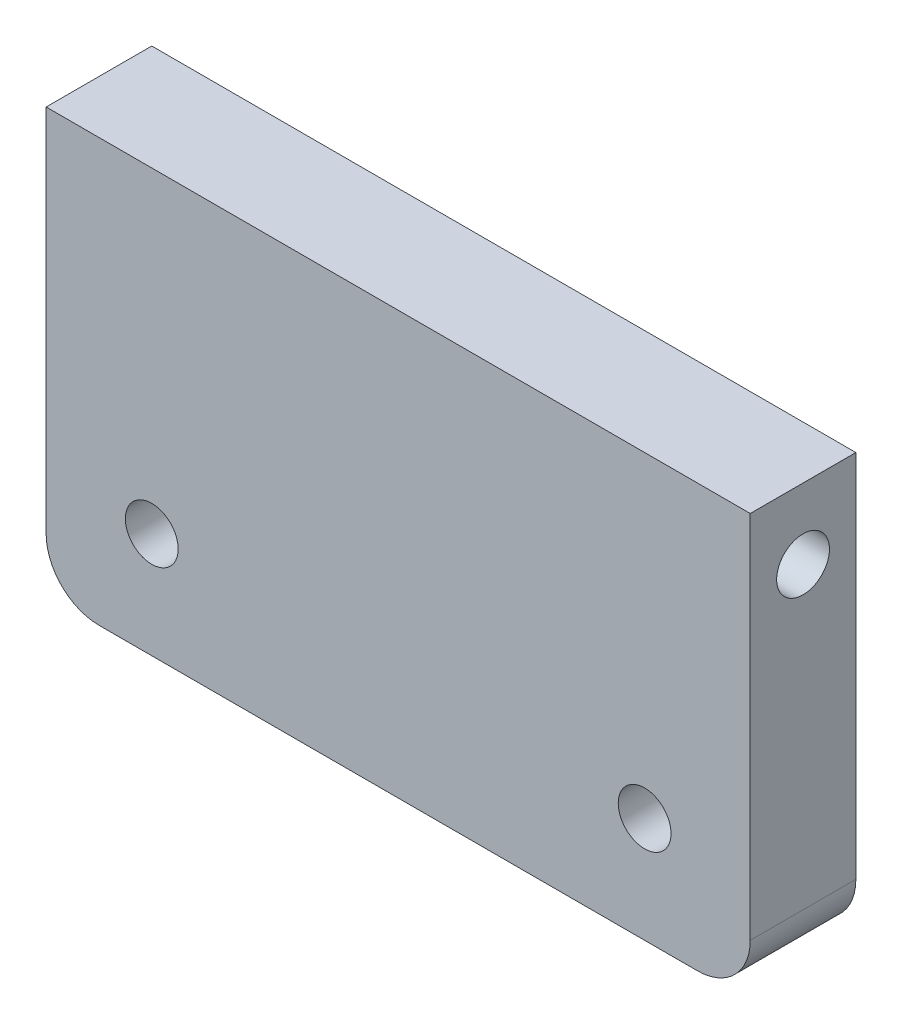
SolidWorks part; units mm, degrees
ref_plane "Front Plane" through (0, 0, 0) normal (0, 0, 1) x (1, 0, 0)
ref_plane "Top Plane" through (0, 0, 0) normal (0, 1, 0) x (1, 0, 0)
ref_plane "Right Plane" through (0, 0, 0) normal (1, 0, 0) x (0, 0, -1)
sketch "Sketch2" plane through (0, 0, 0) normal (0, 0, 1) x (1, 0, 0)
  line L0 (0, 38.1) -> (0, -38.1) construction
  line L1 (-63.5, 38.1) -> (63.5, 38.1)
  line L2 (-63.5, 38.1) -> (-63.5, -28.575)
  line L3 (-53.975, -38.1) -> (53.975, -38.1)
  line L4 (63.5, 38.1) -> (63.5, -28.575)
  line L5 (-63.5, 38.1) -> (63.5, -38.1) construction
  line L6 (-63.5, -38.1) -> (63.5, 38.1) construction
  circle A0 centre (-44.45, -19.05) radius 4.7625
  circle A1 centre (44.45, -19.05) radius 4.7625
  arc A2 (63.5, -28.575) -> (53.975, -38.1) centre (53.975, -28.575) cw
  arc A3 (-63.5, -28.575) -> (-53.975, -38.1) centre (-53.975, -28.575) ccw
  point P0 (0, 0)
  point P12 (0, 0)
  point P13 (-38.1, -19.05)
  point P14 (-44.45, -19.05)
  dimension "D5" = 9.525
  dimension "D6" = 9.525
  dimension "D1" = 76.2
  dimension "D2" = 127
  dimension "D3" = 44.45
  dimension "D4" = 19.05
extrude "Boss-Extrude1" add sketch "Sketch2" along normal blind 19.05
sketch "Sketch3" plane through (63.5, 0, 0) normal (1, 0, 0) x (0, 0, -1)
  line L0 (-19.05, 38.1) -> (0, 38.1) construction
  line L1 (-9.525, 38.1) -> (-9.525, 25.4) construction
  circle A0 centre (-9.525, 25.4) radius 4.7625
  point P4 (-10.4046, 25.4)
  dimension "D1" = 9.525
  dimension "D2" = 12.7
extrude "Cut-Extrude1" cut sketch "Sketch3" against normal blind 139.7
